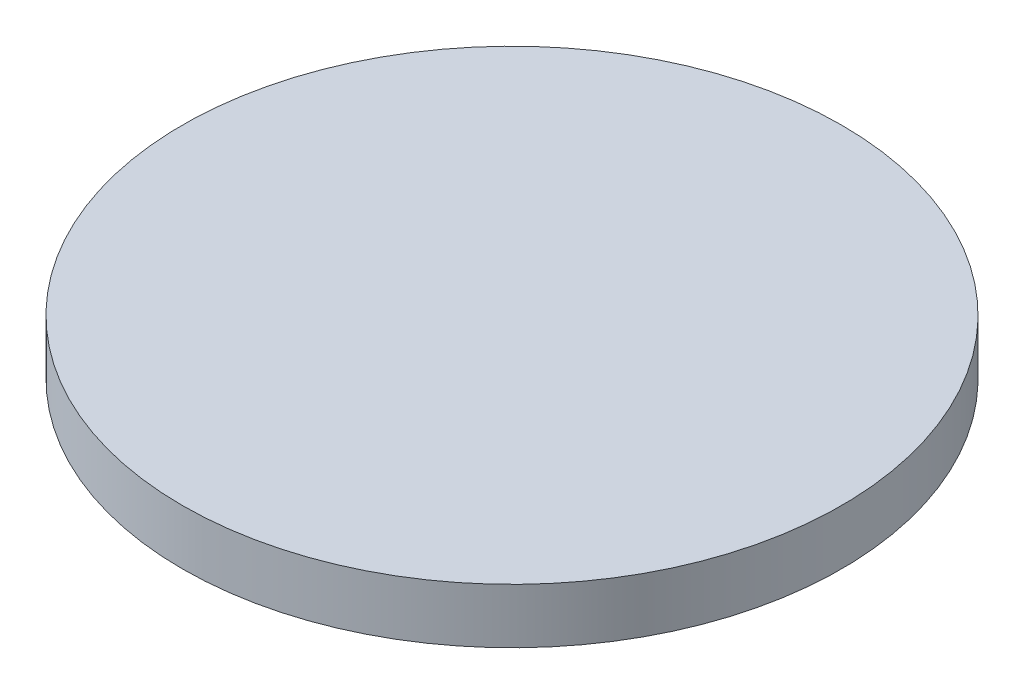
SolidWorks part; units mm, degrees
ref_plane "Front Plane" through (0, 0, 0) normal (0, 0, 1) x (1, 0, 0)
ref_plane "Top Plane" through (0, 0, 0) normal (0, 1, 0) x (1, 0, 0)
ref_plane "Right Plane" through (0, 0, 0) normal (1, 0, 0) x (0, 0, -1)
sketch "Sketch1" plane through (0, 0, 0) normal (0, 1, 0) x (1, 0, 0)
  circle A0 centre (-30.6001, 32.3321) radius 60
extrude "Boss-Extrude1" add sketch "Sketch1" along normal blind 10 contours A0
